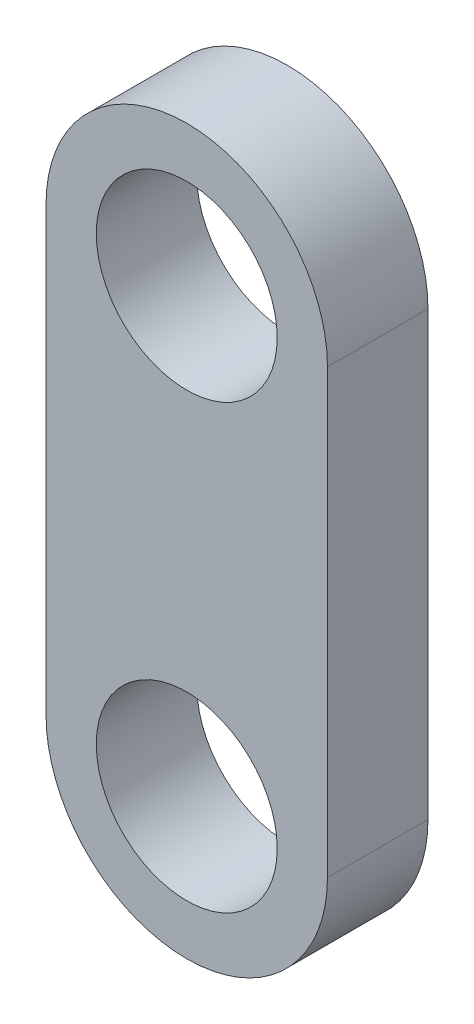
SolidWorks part; units mm, degrees
ref_plane "Front Plane" through (0, 0, 0) normal (0, 0, 1) x (1, 0, 0)
ref_plane "Top Plane" through (0, 0, 0) normal (0, 1, 0) x (1, 0, 0)
ref_plane "Right Plane" through (0, 0, 0) normal (1, 0, 0) x (0, 0, -1)
sketch "Sketch2" plane through (0, 0, 0) normal (0, 0, 1) x (1, 0, 0)
  line L0 (0, 0) -> (0, -11) construction
  line L1 (3.5, -11) -> (-3.5, -11) construction
  line L2 (0, 0) -> (0, 3.5) construction
  line L3 (3.5, 0) -> (-3.5, 0) construction
  line L4 (-3.5, 0) -> (-3.5, -11)
  line L5 (3.5, -11) -> (3.5, 0)
  circle A0 centre (0, 0) radius 2.25
  circle A1 centre (0, -11) radius 2.25
  arc A2 (3.5, 0) -> (-3.5, 0) centre (0, 0) ccw
  arc A3 (3.5, -11) -> (-3.5, -11) centre (0, -11) cw
  point P11 (0, 4.7871)
  dimension "D2" = 4.5
  dimension "D3" = 3.5
  dimension "D1" = 11
extrude "Boss-Extrude1" add sketch "Sketch2" along normal blind 2.5
